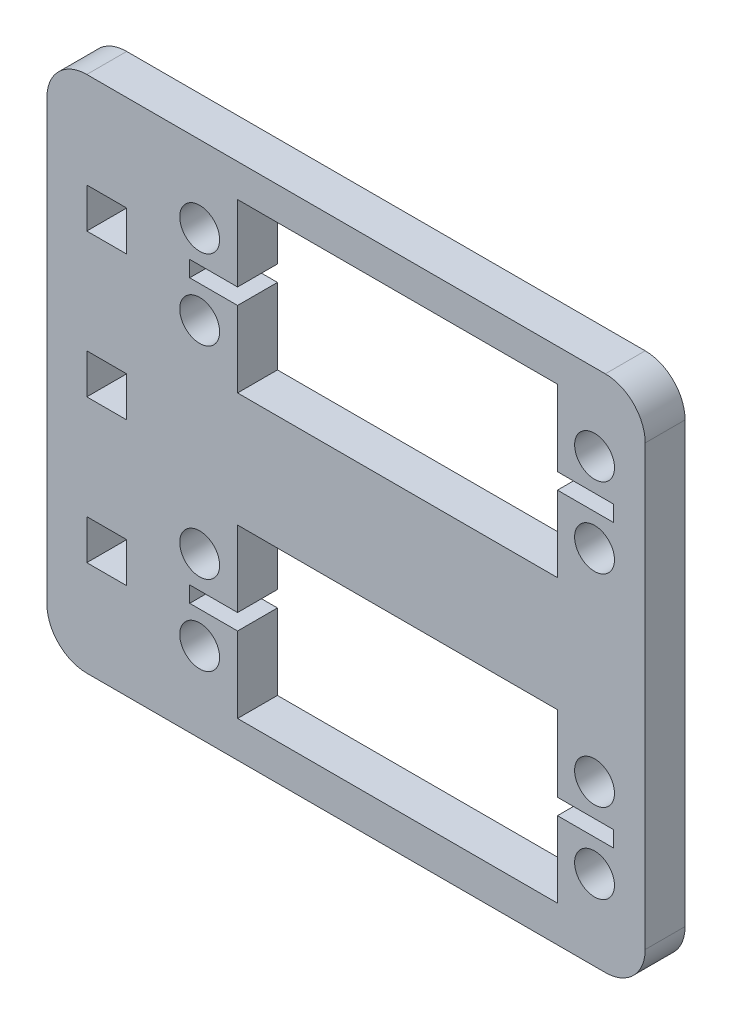
SolidWorks part; units mm, degrees
ref_plane "前视基准面" through (0, 0, 0) normal (0, 0, 1) x (1, 0, 0)
ref_plane "上视基准面" through (0, 0, 0) normal (0, 1, 0) x (1, 0, 0)
ref_plane "右视基准面" through (0, 0, 0) normal (1, 0, 0) x (0, 0, -1)
sketch "草图4" plane through (0, 0, 0) normal (0, 0, 1) x (1, 0, 0)
  line L0 (-30.5142, -31.0858) -> (29.4858, -31.0858)
  line L5 (29.4858, -31.0858) -> (29.4858, 33.9142)
  line L6 (29.4858, 33.9142) -> (-30.5142, 33.9142)
  line L8 (-27.6142, -17.0508) -> (-21.6142, -17.0508)
  line L9 (-21.6142, -15.0508) -> (-27.6142, -15.0508)
  line L10 (-27.6142, -15.0508) -> (-27.6142, -17.0508)
  line L11 (-21.6142, -17.0508) -> (-21.6142, -26.5508)
  line L12 (-21.6142, -26.5508) -> (18.4858, -26.5508)
  line L13 (18.4858, -26.5508) -> (18.4858, -17.0508)
  line L14 (18.4858, -17.0508) -> (25.4858, -17.0508)
  line L15 (25.4858, -17.0508) -> (25.4858, -15.0508)
  line L16 (25.4858, -15.0508) -> (18.4858, -15.0508)
  line L17 (18.4858, -15.0508) -> (18.4858, -5.5508)
  line L18 (18.4858, -5.5508) -> (-21.6142, -5.5508)
  line L19 (-21.6142, -5.5508) -> (-21.6142, -15.0508)
  line L20 (18.4858, 29.7892) -> (-21.6142, 29.7892)
  line L21 (18.4858, 20.2892) -> (18.4858, 29.7892)
  line L22 (25.4858, 20.2892) -> (18.4858, 20.2892)
  line L23 (25.4858, 18.2892) -> (25.4858, 20.2892)
  line L24 (18.4858, 18.2892) -> (25.4858, 18.2892)
  line L25 (18.4858, 8.7892) -> (18.4858, 18.2892)
  line L26 (-21.6142, 8.7892) -> (18.4858, 8.7892)
  line L27 (-21.6142, 18.2892) -> (-21.6142, 8.7892)
  line L28 (-27.6142, 18.2892) -> (-21.6142, 18.2892)
  line L29 (-27.6142, 20.2892) -> (-27.6142, 18.2892)
  line L30 (-21.6142, 20.2892) -> (-27.6142, 20.2892)
  line L31 (-21.6142, 29.7892) -> (-21.6142, 20.2892)
  line L33 (-30.5142, 33.9142) -> (-45.5142, 33.9142)
  line L35 (-30.5142, -31.0858) -> (-45.5142, -31.0858)
  line L36 (-45.5142, 33.9142) -> (-45.5142, -31.0858)
  circle A0 centre (23.1358, 24.2892) radius 2.5
  circle A1 centre (23.1358, 14.2892) radius 2.5
  circle A2 centre (23.1358, -11.0508) radius 2.5
  circle A3 centre (23.1358, -21.0508) radius 2.5
  circle A4 centre (-26.3642, -21.0508) radius 2.5
  circle A5 centre (-26.3642, -11.0508) radius 2.5
  circle A6 centre (-26.3642, 14.2892) radius 2.5
  circle A7 centre (-26.3642, 24.2892) radius 2.5
  dimension "D1" = 65
  dimension "D2" = 15
extrude "凸台-拉伸1" add sketch "草图4" along normal blind 5
sketch "草图5" plane through (0, 0, 0) normal (0, 0, -1) x (-1, 0, 0)
  line L0 (45.5142, 33.9142) -> (40.5142, 33.9142)
  line L1 (-29.4858, 33.9142) -> (45.5142, 33.9142) construction
  line L2 (40.5142, 33.9142) -> (40.5142, -31.0858) construction
  line L3 (45.5142, -31.0858) -> (-29.4858, -31.0858) construction
  line L4 (40.5142, -31.0858) -> (35.5142, -31.0858) construction
  line L5 (35.5142, -31.0858) -> (35.5142, 33.9142) construction
  line L6 (35.5142, 33.9142) -> (40.5142, 33.9142) construction
  line L7 (35.5142, 33.9142) -> (35.5142, 21.9142) construction
  line L8 (35.5142, 21.9142) -> (40.5142, 21.9142)
  line L9 (40.5142, 21.9142) -> (40.5142, 16.9142)
  line L10 (40.5142, 16.9142) -> (35.5142, 16.9142)
  line L11 (35.5142, 16.9142) -> (35.5142, 21.9142)
  line L12 (40.5142, 1.4142) -> (40.5142, 3.9142)
  line L13 (40.5142, 3.9142) -> (35.5142, 3.9142)
  line L14 (35.5142, 3.9142) -> (35.5142, -1.0858)
  line L15 (35.5142, -1.0858) -> (40.5142, -1.0858)
  line L16 (40.5142, -1.0858) -> (40.5142, 3.9142)
  line L17 (35.5142, -31.0858) -> (35.5142, -19.0858)
  line L18 (35.5142, -19.0858) -> (40.5142, -19.0858)
  line L19 (40.5142, -19.0858) -> (40.5142, -14.0858)
  line L20 (40.5142, -14.0858) -> (35.5142, -14.0858)
  line L21 (35.5142, -14.0858) -> (35.5142, -19.0858)
  dimension "D1" = 5
  dimension "D2" = 5
  dimension "D3" = 12
  dimension "D4" = 5
  dimension "D5" = 2.5
  dimension "D6" = 5
  dimension "D7" = 12
  dimension "D8" = 5
extrude "切除-拉伸5" cut sketch "草图5" against normal blind 5 contours L15 L16 L12 L13 L14 | L11 L10 L9 L8 | L20 L21 L18 L19
fillet "圆角1" radius 5 4 edges at (-45.5142, 33.9142, 2.5) (-45.5142, -31.0858, 2.5) (29.4858, -31.0858, 2.5) (29.4858, 33.9142, 2.5)
